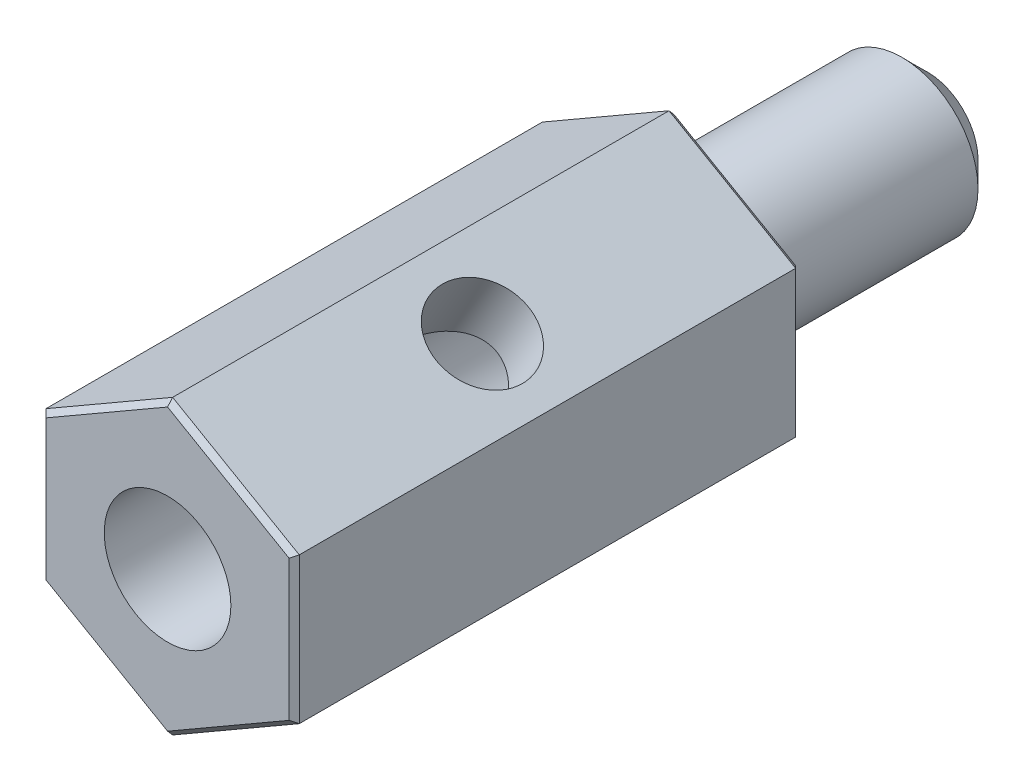
SolidWorks part; units mm, degrees
ref_plane "Płaszczyzna przednia" through (0, 0, 0) normal (0, 0, 1) x (1, 0, 0)
ref_plane "Płaszczyzna górna" through (0, 0, 0) normal (0, 1, 0) x (1, 0, 0)
ref_plane "Płaszczyzna prawa" through (0, 0, 0) normal (1, 0, 0) x (0, 0, -1)
sketch "Szkic1" plane through (0, 0, 0) normal (0, 0, 1) x (1, 0, 0)
  line L1 (0, 2.8868) -> (-2.5, 1.4434)
  line L2 (-2.5, 1.4434) -> (-2.5, -1.4434)
  line L3 (-2.5, -1.4434) -> (0, -2.8868)
  line L4 (0, -2.8868) -> (2.5, -1.4434)
  line L5 (2.5, -1.4434) -> (2.5, 1.4434)
  line L6 (2.5, 1.4434) -> (0, 2.8868)
  circle A0 centre (0, 0) radius 2.5 construction
  dimension "D1" = 5
extrude "Dodanie-wyciągnięcie1" add sketch "Szkic1" along normal blind 10
sketch "Szkic2" plane through (0, 0, 0) normal (0, 0, -1) x (-1, 0, 0)
  circle A0 centre (0, 0) radius 1.5
  dimension "D1" = 3
extrude "Dodanie-wyciągnięcie2" add sketch "Szkic2" along normal blind 5
chamfer "Sfazowanie2" distance 0.5 angle 45 1 edges at (-1.5, 0, -5)
hole_wizard "Otwór gwintowany M31" positions "Szkic27" profile "Szkic26" tap size "M3" standard "ISO"
sketch "Szkic27" plane through (0, 0, 10) normal (0, 0, 1) x (1, 0, 0)
  point P0 (0, 0)
sketch "Szkic26" plane through (0, 0, 10) normal (1, 0, 0) x (0, -1, 0)
  line L0 (0, 0) -> (0, 8.7511)
  line L1 (0, 8.7511) -> (1.25, 8)
  line L2 (1.25, 8) -> (1.25, 0)
  line L5 (1.25, 0) -> (0, 0)
  line L10 (0, 8.7511) -> (-1.25, 8) construction
  line L11 (0, -6.35) -> (0, 107.95) construction
  dimension "Średnica wiertła gwintu" = 2.5
  dimension "Głębokość otworu gwintowanego" = 8
  dimension "Kąt wiertła" = 118
cosmetic thread "Gwint otworu1" parameters "D1"=8, "D2"=3
chamfer "Sfazowanie3" distance 0.1 angle 45 12 edges at (2.5, 0, 10) (1.25, -2.1651, 10) (-1.25, -2.1651, 10) (-2.5, 0, 10) (-1.25, 2.1651, 10) (1.25, 2.1651, 10) (1.25, -2.1651, 0) (2.5, 0, 0) (1.25, 2.1651, 0) (-1.25, 2.1651, 0) (-1.25, -2.1651, 0) (-2.5, 0, 0)
sketch "Szkic29" plane through (1.25, 2.1651, 0) normal (0.5, 0.866, 0) x (0.866, -0.5, 0)
  circle A0 centre (0, -5.0342) radius 0.9123
extrude "Wytnij-wyciągnięcie1" cut sketch "Szkic29" against normal through all
